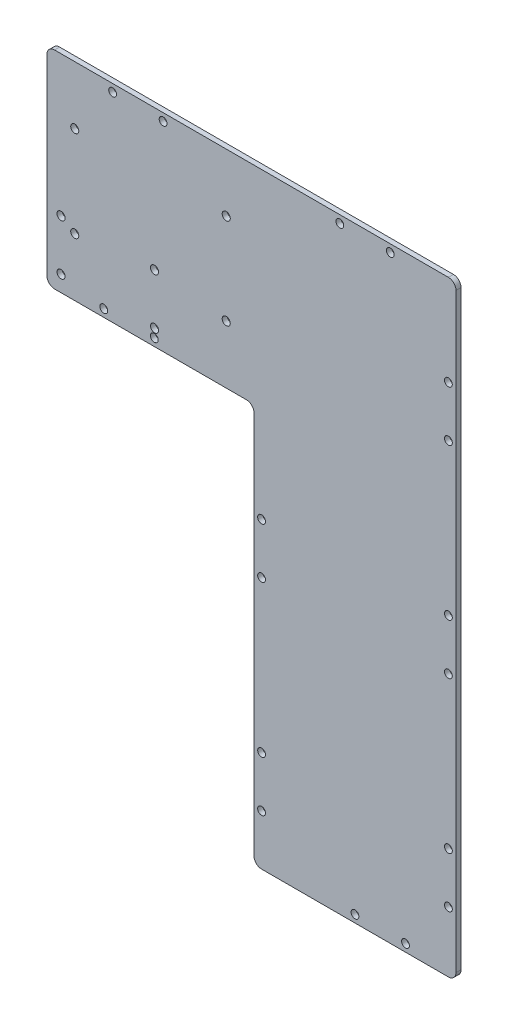
SolidWorks part; units mm, degrees
material "Thornel Mat VMA"
ref_plane "前视基准面" through (0, 0, 0) normal (0, 0, 1) x (1, 0, 0)
ref_plane "上视基准面" through (0, 0, 0) normal (0, 1, 0) x (1, 0, 0)
ref_plane "右视基准面" through (0, 0, 0) normal (1, 0, 0) x (0, 0, -1)
other "Configuration Table"
sketch "草图1" plane through (0, 0, 0) normal (0, 0, 1) x (1, 0, 0)
  line L1 (-41, 41) -> (41, 41)
  line L2 (-41, 41) -> (-41, -41)
  line L3 (-41, -41) -> (41, -41)
  line L4 (41, 41) -> (41, -41)
  line L5 (-41, 41) -> (41, -41) construction
  line L6 (-41, -41) -> (41, 41) construction
  line L7 (121, -199) -> (41, -199)
  line L8 (121, -199) -> (121, 41)
  line L9 (121, 41) -> (41, 41)
  line L10 (41, -199) -> (41, 41)
  line L11 (121, -199) -> (41, 41) construction
  line L12 (121, 41) -> (41, -199) construction
  point P0 (0, 0)
  point P6 (81, -79)
  dimension "D1" = 82
  dimension "D2" = 82
  dimension "D3" = 80
  dimension "D4" = 240
extrude "凸台-拉伸1" add sketch "草图1" along normal blind 2 contours L4 L1 L2 L3 | L10 L7 L8 L9 L4
sketch "草图2" plane through (0, 0, 2) normal (0, 0, 1) x (1, 0, 0)
  line L0 (-41, 41) -> (-41, -41) construction
  line L1 (-41, 41) -> (121, 41) construction
  line L2 (-41, -41) -> (41, -41) construction
  line L3 (121, -199) -> (41, -199) construction
  line L4 (30, 18) -> (-30, 18) construction
  line L5 (30, 18) -> (30, -18) construction
  line L6 (30, -18) -> (-30, -18) construction
  line L7 (-30, 18) -> (-30, -18) construction
  line L8 (30, 18) -> (-30, -18) construction
  line L9 (30, -18) -> (-30, 18) construction
  line L10 (41, -199) -> (41, -41) construction
  line L11 (121, -199) -> (121, 41) construction
  circle A0 centre (-15, 38) radius 1.55
  circle A1 centre (5, 38) radius 1.55
  circle A2 centre (-18.5, -38) radius 1.55
  circle A3 centre (1.5, -38) radius 1.55
  circle A4 centre (-30, 18) radius 1.6
  circle A5 centre (30, 18) radius 1.6
  circle A6 centre (30, -18) radius 1.6
  circle A7 centre (-30, -18) radius 1.6
  circle A8 centre (44, -179) radius 1.55
  circle A9 centre (44, -159) radius 1.55
  circle A10 centre (101, -196) radius 1.55
  circle A11 centre (81, -196) radius 1.55
  circle A12 centre (44, -99) radius 1.55
  circle A13 centre (44, -79) radius 1.55
  circle A14 centre (118, 5) radius 1.55
  circle A15 centre (118, -15) radius 1.55
  circle A16 centre (118, -75) radius 1.55
  circle A17 centre (118, -95) radius 1.55
  circle A18 centre (118, -175) radius 1.55
  circle A19 centre (118, -155) radius 1.55
  circle A20 centre (95, 38) radius 1.55
  circle A21 centre (75, 38) radius 1.55
  point P14 (0, 0)
  dimension "D2" = 20
  dimension "D3" = 3.1
  dimension "D4" = 22.5
  dimension "D5" = 3
  dimension "D6" = 3
  dimension "D7" = 20
  dimension "D8" = 3
  dimension "D9" = 3
  dimension "D12" = 2
  dimension "D14" = 20
  dimension "D15" = 20
  dimension "D18" = 20
  dimension "D19" = 20
  dimension "D20" = 3
  dimension "D21" = 20
  dimension "D22" = 60
  dimension "D23" = 20
  dimension "D24" = 36
  dimension "D25" = 20
  dimension "D26" = 60
  dimension "D27" = 3
  dimension "D28" = 3
  dimension "D29" = 3
  dimension "D30" = 3
  dimension "D31" = 3
  dimension "D32" = 20
  dimension "D33" = 60
  dimension "D34" = 3
  dimension "D35" = 26
  dimension "D36" = 20
  dimension "D1" = 26
  dimension "D10" = 60
  dimension "D11" = 36
  dimension "D16" = 3
  dimension "D17" = 3
  dimension "D13" = 2
extrude "切除-拉伸1" cut sketch "草图2" against normal through all
fillet "圆角1" radius 3 6 edges at (121, 41, 1) (121, -199, 1) (41, -199, 1) (41, -41, 1) (-41, -41, 1) (-41, 41, 1)
sketch "草图4" plane through (0, 0, 2) normal (0, 0, 1) x (1, 0, 0)
  circle A0 centre (-35.4345, -34.6245) radius 1.6
  circle A1 centre (1.5955, -34.6245) radius 1.6
  circle A2 centre (1.5955, -14.6245) radius 1.6
  circle A3 centre (-35.4345, -14.6245) radius 1.6
  dimension "D3" = 37.03
  dimension "D4" = 3.2
  dimension "D1" = 2
  dimension "D2" = 2
extrude "切除-拉伸2" cut sketch "草图4" against normal through all
